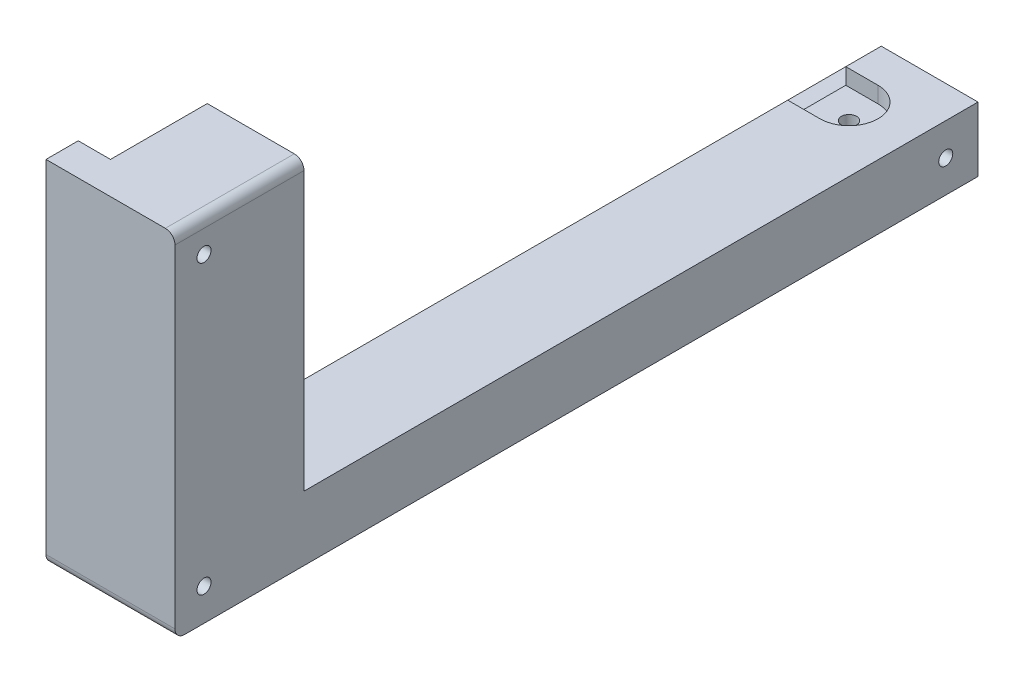
SolidWorks part; units mm, degrees
material "ABS"
ref_plane "Front Plane" through (0, 0, 0) normal (0, 0, 1) x (1, 0, 0)
ref_plane "Top Plane" through (0, 0, 0) normal (0, 1, 0) x (1, 0, 0)
ref_plane "Right Plane" through (0, 0, 0) normal (1, 0, 0) x (0, 0, -1)
sketch "Sketch1" plane through (0, 0, 0) normal (0, 1, 0) x (1, 0, 0)
  line L1 (-20, -124.5) -> (20, -124.5)
  line L2 (-20, -124.5) -> (-20, 124.5)
  line L3 (-20, 124.5) -> (20, 124.5)
  line L4 (20, -124.5) -> (20, 124.5)
  line L5 (-20, -124.5) -> (20, 124.5) construction
  line L6 (-20, 124.5) -> (20, -124.5) construction
  point P0 (0, 0)
  dimension "D1" = 40
  dimension "D2" = 249
extrude "Boss-Extrude1" add sketch "Sketch1" along normal blind 20
sketch "Sketch2" plane through (0, 20, 0) normal (0, 1, 0) x (1, 0, 0)
  line L0 (20, -124.5) -> (20, 124.5) construction
  line L1 (-20, -124.5) -> (20, -124.5)
  line L2 (-20, -124.5) -> (-20, -84.5)
  line L3 (-20, -84.5) -> (20, -84.5)
  line L4 (20, -124.5) -> (20, -84.5)
  dimension "D1" = 40
extrude "Boss-Extrude2" add sketch "Sketch2" along normal blind 89.09
sketch "Sketch3" plane through (0, 20, 0) normal (0, 1, 0) x (1, 0, 0)
  line L1 (-10, 124.5) -> (-20, 124.5)
  line L2 (-10, 124.5) -> (-10, -114.5)
  line L3 (-10, -114.5) -> (-20, -114.5)
  line L4 (-20, 124.5) -> (-20, -114.5)
  line L6 (-20, -124.5) -> (20, -124.5) construction
  dimension "D1" = 10
  dimension "D2" = 10
extrude "Cut-Extrude1" cut sketch "Sketch3" against normal blind 10 and the other way blind 100
sketch "Sketch6" plane through (-10, 0, 0) normal (-1, 0, 0) x (0, 0, 1)
  line L0 (84.5, 109.09) -> (84.5, 20) construction
  line L1 (114.5, 20) -> (84.5, 20)
  line L2 (114.5, 20) -> (114.5, 40)
  line L3 (114.5, 40) -> (84.5, 40)
  line L4 (84.5, 20) -> (84.5, 40)
  line L5 (114.5, 109.09) -> (114.5, 10) construction
  dimension "D1" = 20
extrude "Cut-Extrude4" cut sketch "Sketch6" against normal blind 20
sketch "Sketch4" plane through (0, 20, 0) normal (0, 1, 0) x (1, 0, 0)
  line L0 (20, -84.5) -> (20, 124.5) construction
  line L1 (20, 124.5) -> (-10, 124.5) construction
  line L2 (-20, 124.5) -> (-20, -114.5) construction
  circle A0 centre (0, 104.5) radius 2.35
  circle A1 centre (0, -105.5) radius 2.35
  dimension "D1" = 20
  dimension "D3" = 4.7
  dimension "D4" = 230
  dimension "D2" = 20
  dimension "D5" = 20
extrude "Cut-Extrude2" cut sketch "Sketch4" against normal blind 23
sketch "Sketch5" plane through (0, 20, 0) normal (0, 1, 0) x (1, 0, 0)
  line L0 (0, 95.5) -> (-10, 95.5)
  line L13 (-10, -114.5) -> (-10, 124.5) construction
  line L14 (-10, 95.5) -> (-10, 113.5)
  line L15 (-10, 113.5) -> (0, 113.5)
  line L16 (0, -96.5) -> (-20, -96.5)
  line L17 (-20, -114.5) -> (-20, -124.5) construction
  line L18 (-20, -96.5) -> (-20, -114.5)
  line L19 (-20, -114.5) -> (0, -114.5)
  arc A2 (0, 95.5) -> (0, 113.5) centre (0, 104.5) ccw
  arc A3 (0, -114.5) -> (0, -96.5) centre (0, -105.5) ccw
  dimension "D1" = 9
  dimension "D2" = 9
extrude "Cut-Extrude3" cut sketch "Sketch5" against normal blind 5
sketch "Sketch7" plane through (20, 0, 0) normal (1, 0, 0) x (0, 0, -1)
  line L0 (-124.5, 109.09) -> (-124.5, 0) construction
  line L1 (-124.5, 0) -> (124.5, 0) construction
  line L2 (124.5, 20) -> (124.5, 0) construction
  line L3 (-124.5, 109.09) -> (-84.5, 109.09) construction
  line L4 (-124.5, 109.09) -> (-124.5, 0) construction
  circle A0 centre (114.5, 10) radius 2.175
  circle A1 centre (-115.5, 10) radius 2.175
  circle A2 centre (-115.5, 99.09) radius 2.175
  dimension "D1" = 9
  dimension "D5" = 4.35
  dimension "D6" = 10
  dimension "D2" = 10
  dimension "D3" = 10
  dimension "D4" = 10
  dimension "D7" = 9
extrude "Cut-Extrude5" cut sketch "Sketch7" against normal blind 8
fillet "Fillet1" radius 3 2 edges at (0, 0, 124.5) (20, 109.09, 104.5)
